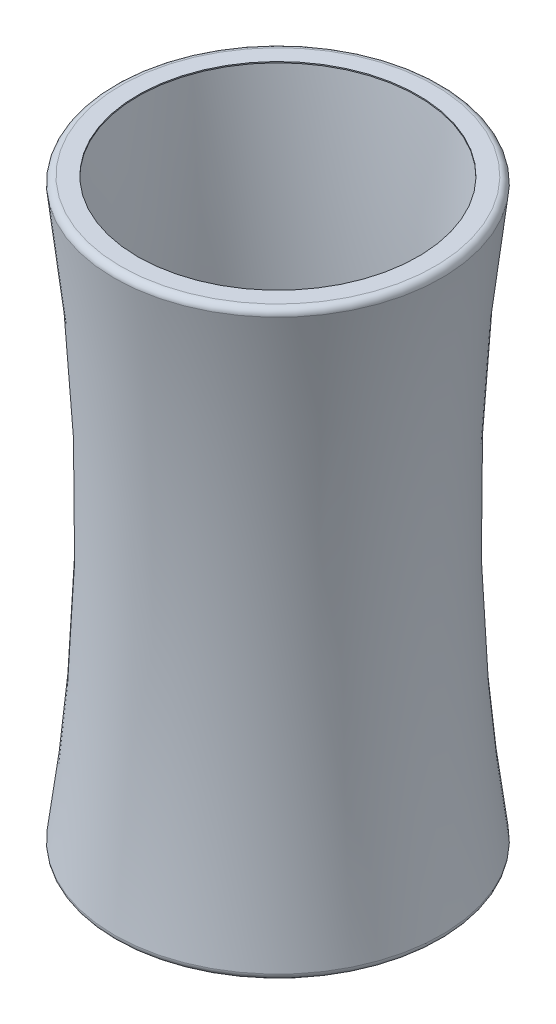
SolidWorks part; units mm, degrees
ref_plane "Front Plane" through (0, 0, 0) normal (0, 0, 1) x (1, 0, 0)
ref_plane "Top Plane" through (0, 0, 0) normal (0, 1, 0) x (1, 0, 0)
ref_plane "Right Plane" through (0, 0, 0) normal (1, 0, 0) x (0, 0, -1)
sketch "Sketch1" plane through (0, 0, 0) normal (0, 0, 1) x (1, 0, 0)
  line L0 (0, 0) -> (0, -200.1448) construction
  line L1 (12.5, -114.6866) -> (12.5, -114.7866)
  line L2 (12.5, -114.7866) -> (14.0045, -114.7866)
  line L3 (14.5042, -115.2863) -> (14.5042, -115.9984) construction
  line L4 (12.5, -114.6866) -> (14.0045, -114.6866)
  line L5 (14.6042, -115.2863) -> (14.6042, -166.0369) construction
  line L6 (14.0045, -166.5366) -> (11.3189, -166.5366)
  line L7 (14.0045, -166.6366) -> (11.3189, -166.6366)
  line L8 (11.3189, -166.5366) -> (11.3189, -166.6366)
  line L9 (14.5042, -115.9984) -> (14.5042, -165.3249) construction
  line L10 (14.5042, -165.3249) -> (14.5042, -166.0369) construction
  arc A0 (14.0045, -114.7866) -> (14.5042, -115.2863) centre (14.0045, -115.2863) cw
  arc A1 (14.0045, -114.6866) -> (14.6042, -115.2863) centre (14.0045, -115.2863) cw
  arc A2 (14.5042, -166.0369) -> (14.0045, -166.5366) centre (14.0045, -166.0369) cw
  arc A3 (14.6042, -166.0369) -> (14.0045, -166.6366) centre (14.0045, -166.0369) cw
  arc A4 (14.5042, -115.2863) -> (14.5042, -166.0369) centre (192.7066, -140.6616) ccw
  arc A5 (14.6042, -115.2863) -> (14.6042, -166.0369) centre (192.7066, -140.6616) ccw
  dimension "D1" = 0.1
  dimension "D2" = 12.5
  dimension "D3" = 180
  dimension "D6" = 51.75
revolve "Revolve1" add sketch "Sketch1" angle 360 about L0
